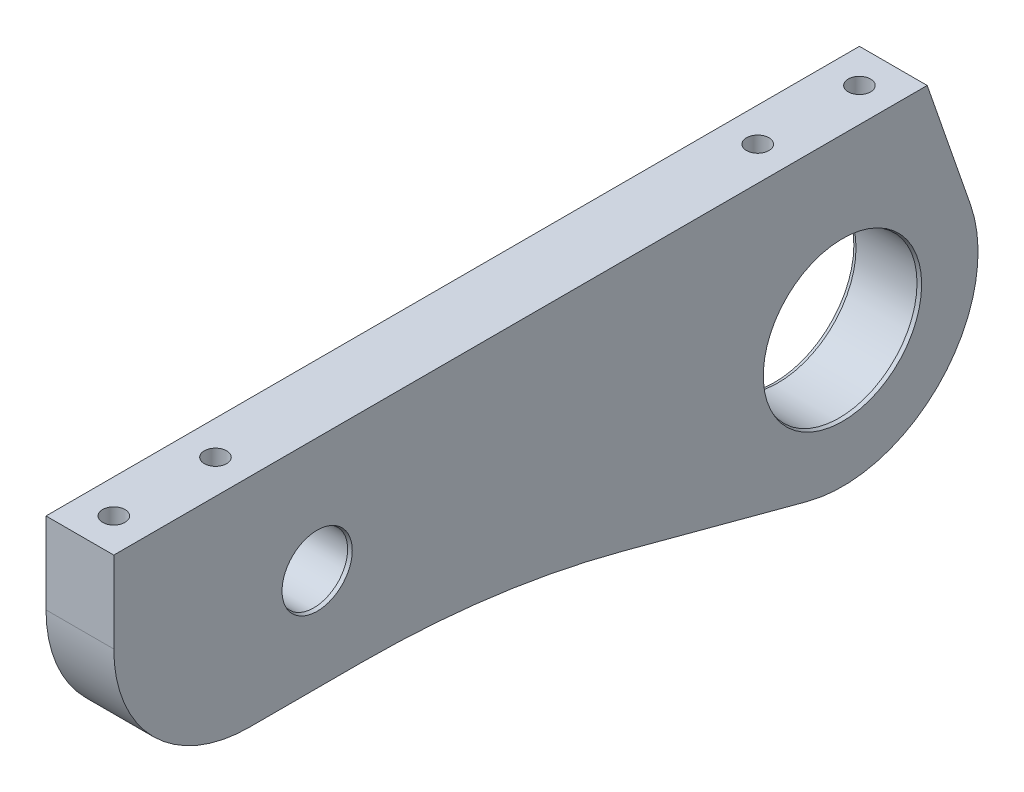
SolidWorks part; units mm, degrees
material "ALUMINIUM,  6082-T6"
ref_plane "Front Plane" through (0, 0, 0) normal (0, 0, 1) x (1, 0, 0)
ref_plane "Top Plane" through (0, 0, 0) normal (0, 1, 0) x (1, 0, 0)
ref_plane "Right Plane" through (0, 0, 0) normal (1, 0, 0) x (0, 0, -1)
sketch "Sketch1" plane through (0, 0, 0) normal (1, 0, 0) x (0, 0, -1)
  line L0 (-60, 0) -> (60, 0)
  line L1 (60, 0) -> (66.3964, -18.4482)
  line L4 (-60, 0) -> (-60, -32)
  line L5 (-3.8164, -32) -> (42.3411, -44.3232)
  line L6 (-3.8164, -32) -> (-60, -32)
  line L7 (-3.8164, -32) -> (-60, -17) construction
  arc A0 (42.3411, -44.3232) -> (66.3964, -18.4482) centre (47.5, -25) ccw
  circle A1 centre (-30, -17) radius 5 construction
  dimension "D3" = 20
  dimension "D7" = 10
  dimension "D1" = 17
  dimension "D2" = 25
  dimension "D4" = 120
  dimension "D5" = 12.5
  dimension "D6" = 32
  dimension "D8" = 30
  dimension "D9" = 10
extrude "Boss-Extrude1" add sketch "Sketch1" along normal mid plane 10
sketch "Sketch4" plane through (5, 0, 0) normal (1, 0, 0) x (0, 0, -1)
  circle A0 centre (47.5, -25) radius 11.5
  arc A1 (42.3411, -44.3232) -> (66.3964, -18.4482) centre (47.5, -25) ccw construction
  dimension "D1" = 23
extrude "Cut-Extrude1" cut sketch "Sketch4" against normal blind 10
hole_wizard "M4 Tapped Hole1" positions "Sketch2" profile "Sketch3" tap size "M4" standard "ISO"
sketch "Sketch2" plane through (0, 0, 0) normal (0, 1, 0) x (1, 0, 0)
  line L0 (0, 55) -> (0, 40) construction
  line L1 (0, 40) -> (0, -40) construction
  line L2 (0, -40) -> (0, -55) construction
  line L4 (5, 60) -> (-5, 60) construction
  point P0 (0, -55)
  point P2 (0, -40)
  point P4 (0, 40)
  point P6 (0, 55)
  dimension "D1" = 15
  dimension "D2" = 5
sketch "Sketch3" plane through (0, 0, 55) normal (1, 0, 0) x (0, 0, 1)
  line L0 (0, 0) -> (0, 12.4914)
  line L1 (0, 12.4914) -> (1.65, 11.5)
  line L2 (1.65, 11.5) -> (1.65, 0)
  line L5 (1.65, 0) -> (0, 0)
  line L10 (0, 12.4914) -> (-1.65, 11.5) construction
  line L11 (0, -6.35) -> (0, 107.95) construction
  dimension "Tap Drill Dia." = 3.3
  dimension "Tap Drill Depth" = 11.5
  dimension "Drill Angle" = 118
cosmetic thread "Hole Thread1" parameters "D1"=8, "D2"=4
cosmetic thread "Hole Thread2" parameters "D1"=8, "D2"=4
cosmetic thread "Hole Thread3" parameters "D1"=8, "D2"=4
cosmetic thread "Hole Thread4" parameters "D1"=8, "D2"=4
sketch "Sketch5" plane through (5, 0, 0) normal (1, 0, 0) x (0, 0, -1)
  line L0 (60, 0) -> (-60, 0) construction
  line L1 (-60, 0) -> (-60, -32) construction
  circle A0 centre (-30, -17) radius 5
  dimension "D1" = 10
  dimension "D2" = 17
  dimension "D3" = 30
extrude "Cut-Extrude2" cut sketch "Sketch5" against normal blind 10
fillet "Fillet1" radius 150 1 edges at (0, -32, 3.8164)
fillet "Fillet2" radius 20 1 edges at (0, -32, 60)
chamfer "Chamfer1" distance 0.5 angle 20 4 edges at (5, -17, 25) (-5, -17, 25) (5, -25, -59) (-5, -25, -59)
